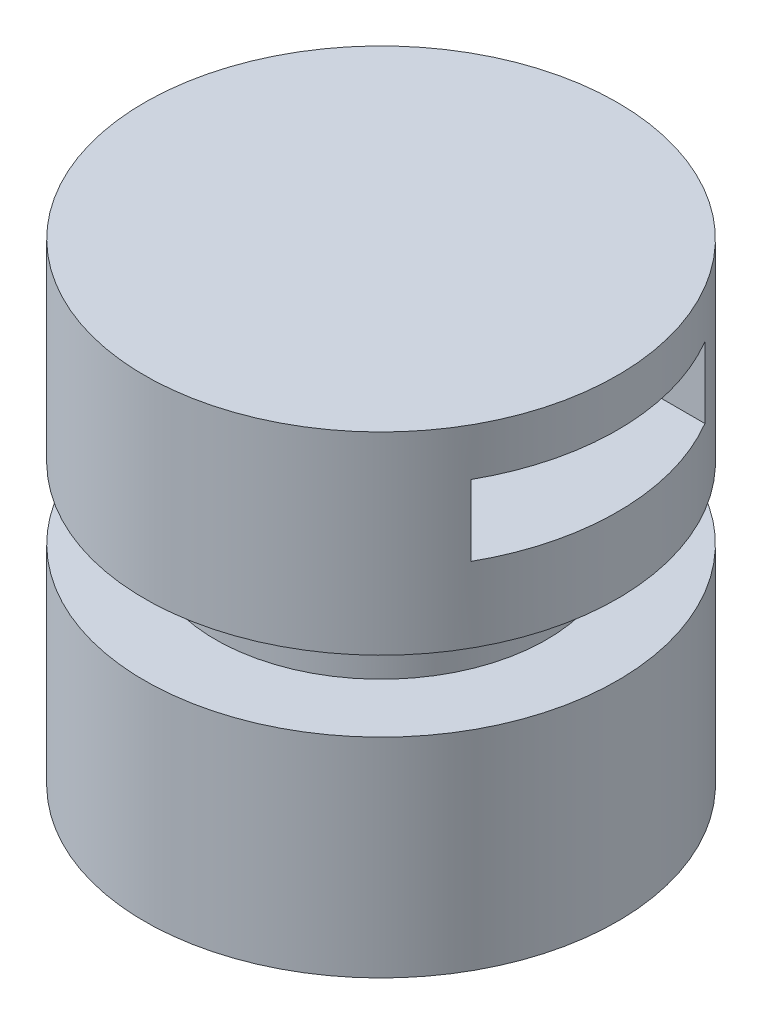
SolidWorks part; units mm, degrees
ref_plane "Front Plane" through (0, 0, 0) normal (0, 0, 1) x (1, 0, 0)
ref_plane "Top Plane" through (0, 0, 0) normal (0, 1, 0) x (1, 0, 0)
ref_plane "Right Plane" through (0, 0, 0) normal (1, 0, 0) x (0, 0, -1)
sketch "Sketch1" plane through (0, 0, 0) normal (1, 0, 0) x (0, 0, -1)
  line L1 (0, 0) -> (-100, 0)
  line L2 (0, 0) -> (0, 200)
  line L3 (0, 200) -> (-100, 200)
  line L4 (-100, 0) -> (-100, 200)
  point P5 (108.8721, -67.2415)
  dimension "D1" = 100
  dimension "D2" = 200
revolve "Revolve1" add sketch "Sketch1" angle 360 about L2
sketch "Sketch2" plane through (0, 0, 0) normal (1, 0, 0) x (0, 0, -1)
  line L0 (0, 0) -> (0, 198.0229) construction
  line L1 (-70, 118.2207) -> (-100, 118.2207)
  line L2 (-70, 118.2207) -> (-70, 88.2207)
  line L3 (-70, 88.2207) -> (-100, 88.2207)
  line L4 (-100, 118.2207) -> (-100, 88.2207)
  line L5 (-100, 200) -> (-100, 0) construction
  line L7 (-100, 200) -> (-100, 0) construction
  line L9 (-100, 103.2207) -> (-70, 103.2207) construction
  point P4 (-85, 88.2207)
  point P12 (0, 0)
  point P13 (0, 0)
  point P20 (281.5166, 86.0499)
  dimension "D1" = 70
  dimension "D2" = 88.2207
revolve "Cut-Revolve1" cut sketch "Sketch2" angle 360 about L0
sketch "Sketch4" plane through (0, 0, 0) normal (1, 0, 0) x (0, 0, -1)
  line L0 (0, 200) -> (0, 118.2207) construction
  line L1 (50.8852, 150) -> (-49.1148, 150)
  line L2 (50.8852, 150) -> (50.8852, 180)
  line L3 (50.8852, 180) -> (-49.1148, 180)
  line L4 (-49.1148, 150) -> (-49.1148, 180)
  line L5 (100, 200) -> (-100, 200) construction
  line L6 (-70, 118.2207) -> (70, 118.2207) construction
  line L7 (-100, 159.1104) -> (100, 159.1104) construction
  line L8 (-100, 200) -> (-100, 118.2207) construction
  line L9 (100, 118.2207) -> (100, 200) construction
  point P13 (-288.5843, 268.3018)
  dimension "D1" = 30
  dimension "D2" = 100
  dimension "D3" = 20
  dimension "D4" = 50.8852
extrude "Cut-Extrude1" cut sketch "Sketch4" against normal through all both and the other way through all contours L2 L1 L4 L3
